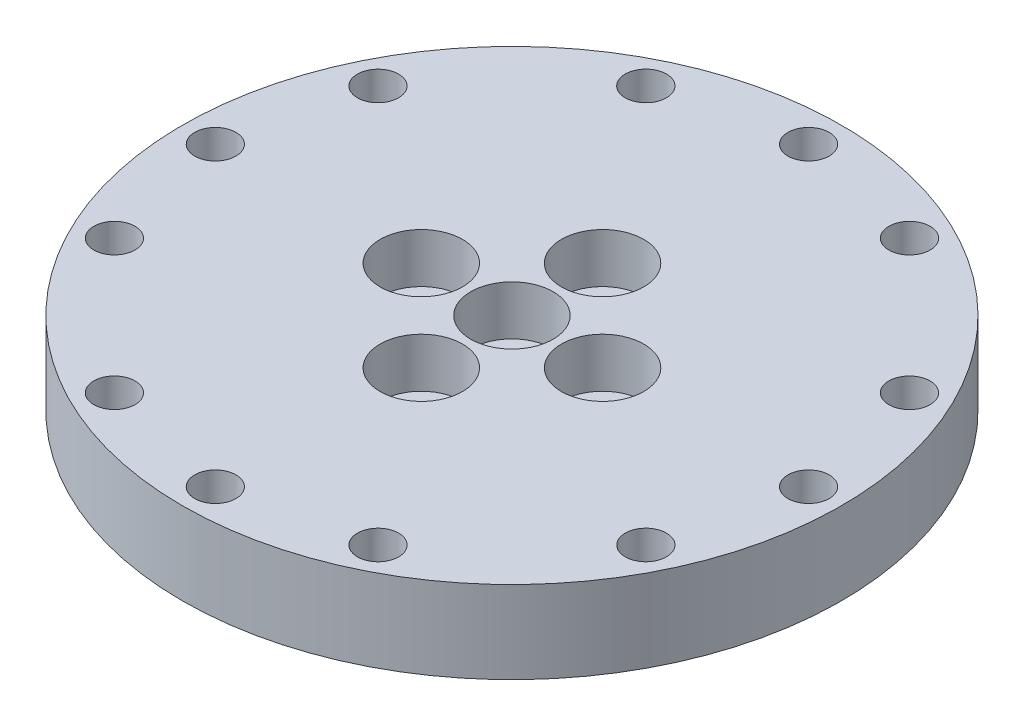
SolidWorks part; units mm, degrees
ref_plane "Front Plane" through (0, 0, 0) normal (0, 0, 1) x (1, 0, 0)
ref_plane "Top Plane" through (0, 0, 0) normal (0, 1, 0) x (1, 0, 0)
ref_plane "Right Plane" through (0, 0, 0) normal (1, 0, 0) x (0, 0, -1)
sketch "Sketch1" plane through (0, 0, 0) normal (0, 1, 0) x (1, 0, 0)
  circle A0 centre (0, 0) radius 17.5
  circle A2 centre (0, 0) radius 21.5
  dimension "D1" = 35
extrude "Boss-Extrude1" add sketch "Sketch1" along normal blind 9
sketch "Sketch3" plane through (0, 9, 0) normal (0, 1, 0) x (1, 0, 0)
  circle A0 centre (0, 0) radius 40
  circle A1 centre (0, 0) radius 3.05
  circle A2 centre (-11, 0) radius 3.05
  circle A3 centre (0, -11) radius 3.05
  circle A4 centre (11, 0) radius 3.05
  circle A5 centre (0, 11) radius 3.05
  circle A10 centre (0, 36) radius 2.5
  circle A15 centre (-32.2511, 15.9959) radius 2.4969
  circle A16 centre (-32.2511, -15.9959) radius 2.4995
  circle A17 centre (0, -36) radius 2.5
  circle A20 centre (36, 0) radius 2.5
  circle A21 centre (32.2511, 15.9959) radius 2.5028
  circle A25 centre (32.2511, -15.9959) radius 2.5
  circle A26 centre (-16, 32.2536) radius 2.5036
  circle A27 centre (16, 32.2536) radius 2.5036
  circle A28 centre (-16, -32.25) radius 2.5
  circle A29 centre (16, -32.25) radius 2.5
  circle A30 centre (-36, 0) radius 2.5
extrude "Boss-Extrude2" add sketch "Sketch3" along normal blind 10
sketch "Sketch6" plane through (0, 19, 0) normal (0, 1, 0) x (1, 0, 0)
  circle A0 centre (-11, 0) radius 5
  circle A1 centre (0, 0) radius 5
  circle A3 centre (0, -11) radius 5
  circle A4 centre (11, 0) radius 5
  circle A5 centre (0, 11) radius 5
  circle M7 centre (11, 0) radius 3.05
  circle M8 centre (-11, 0) radius 3.05
  circle M10 centre (0, 0) radius 3.05
  circle M11 centre (0, -11) radius 3.05
  circle M12 centre (0, 11) radius 3.05
extrude "Cut-Extrude1" cut sketch "Sketch6" against normal blind 6 contours A5 M12 | A0 M8 | A1 M10 | A4 M7 | A3 M11
